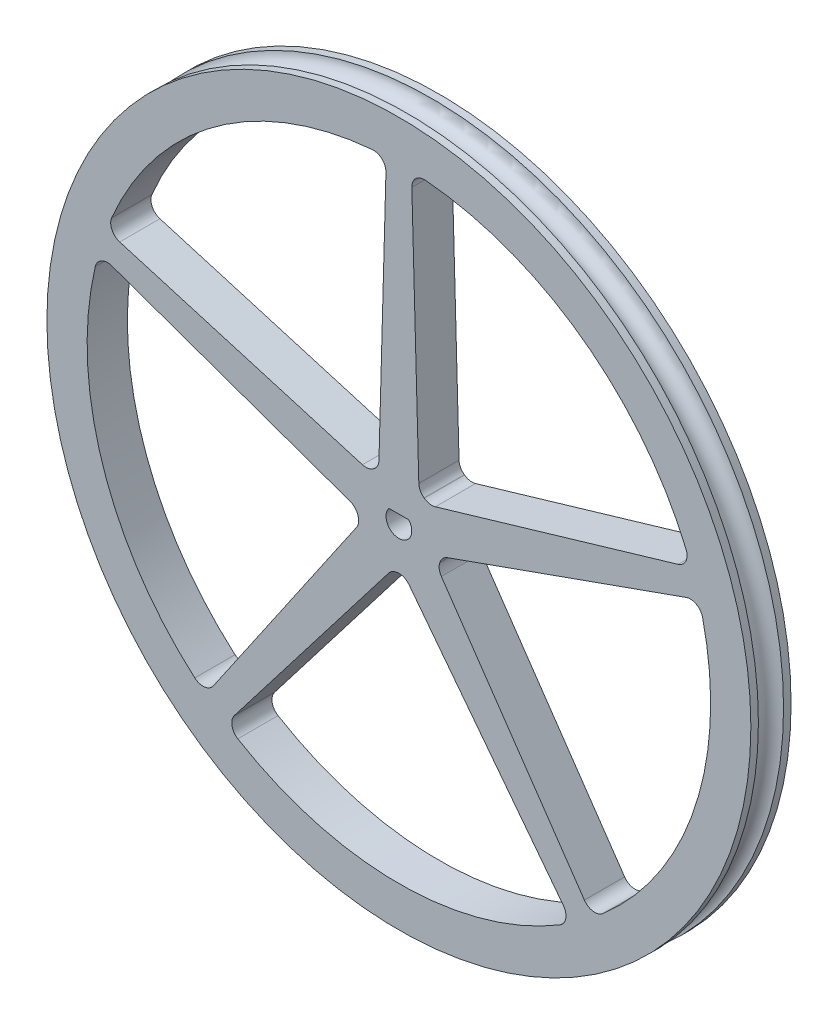
SolidWorks part; units mm, degrees
ref_plane "Front Plane" through (0, 0, 0) normal (0, 0, 1) x (1, 0, 0)
ref_plane "Top Plane" through (0, 0, 0) normal (0, 1, 0) x (1, 0, 0)
ref_plane "Right Plane" through (0, 0, 0) normal (1, 0, 0) x (0, 0, -1)
sketch "Sketch1" plane through (0, 0, 0) normal (0, 0, 1) x (1, 0, 0)
  line L0 (1.2482, 1.0414) -> (-1.2482, 1.0414)
  circle A0 centre (0, 0) radius 1.6256 construction
  arc A1 (1.2482, 1.0414) -> (-1.2482, 1.0414) centre (0, 0) cw
  circle A2 centre (0, 0) radius 44.45
  point P6 (0, 1.6256)
  point P7 (0, -1.6256)
  dimension "D1" = 3.2512
  dimension "D3" = 88.9
  dimension "D2" = 2.667
extrude "Boss-Extrude1" add sketch "Sketch1" along normal mid plane 5.08
sketch "Sketch2" plane through (0, 0, 0) normal (0, 1, 0) x (1, 0, 0)
  line L0 (0, 0) -> (0, 12.7709) construction
  line L1 (44.45, -2.54) -> (44.45, 2.54) construction
  circle A0 centre (44.45, 0) radius 1.5875
  point P6 (44.45, 0)
  dimension "D1" = 3.175
revolve "Cut-Revolve1" cut sketch "Sketch2" angle 360 about L0
sketch "Sketch4" plane through (0, 0, 2.54) normal (0, 0, 1) x (1, 0, 0)
  line L0 (-2.54, 4.8056) -> (-1.5875, 39.338)
  line L1 (1.5875, 39.338) -> (2.54, 4.8056)
  line L2 (0, 39.37) -> (0, 0) construction
  line L3 (37.9032, 10.6463) -> (5.3553, -0.9307)
  line L4 (3.7855, 3.9007) -> (36.9221, 13.6659)
  line L5 (21.838, -32.7582) -> (0.7698, -5.3808)
  line L6 (4.8796, -2.3949) -> (24.4066, -30.892)
  line L7 (-24.4066, -30.892) -> (-4.8796, -2.3949)
  line L8 (-0.7698, -5.3808) -> (-21.838, -32.7582)
  line L9 (-36.9221, 13.6659) -> (-3.7855, 3.9007)
  line L10 (-5.3553, -0.9307) -> (-37.9032, 10.6463)
  circle A0 centre (0, 0) radius 5.4356
  circle A1 centre (0, 0) radius 39.37
  circle A2 centre (0, 0) radius 44.45 construction
  arc A3 (-1.2482, 1.0414) -> (1.2482, 1.0414) centre (0, 0) ccw construction
  point P33 (0, 0)
  dimension "D1" = 5.08
  dimension "D2" = 3.81
  dimension "D3" = 5.08
  dimension "D4" = 3.175
  dimension "D5" = 5
extrude "Cut-Extrude1" cut sketch "Sketch4" against normal through all contours L0 A1 L9 A0 | L4 A1 L1 A0 | L6 A1 L3 A0 | L8 A1 L5 A0 | L10 A1 L7 A0
fillet "Fillet1" radius 1.5875 20 edges at (-3.7855, 3.9007, 0) (-36.9221, 13.6659, 0) (-1.5875, 39.338, 0) (-2.54, 4.8056, 0) (0.7698, -5.3808, 0) (21.838, -32.7582, 0) (-21.838, -32.7582, 0) (-0.7698, -5.3808, 0) (-4.8796, -2.3949, 0) (-24.4066, -30.892, 0) (-37.9032, 10.6463, 0) (-5.3553, -0.9307, 0) (2.54, 4.8056, 0) (1.5875, 39.338, 0) (3.7855, 3.9007, 0) (5.3553, -0.9307, 0) (37.9032, 10.6463, 0) (24.4066, -30.892, 0) (4.8796, -2.3949, 0) (36.9221, 13.6659, 0)
